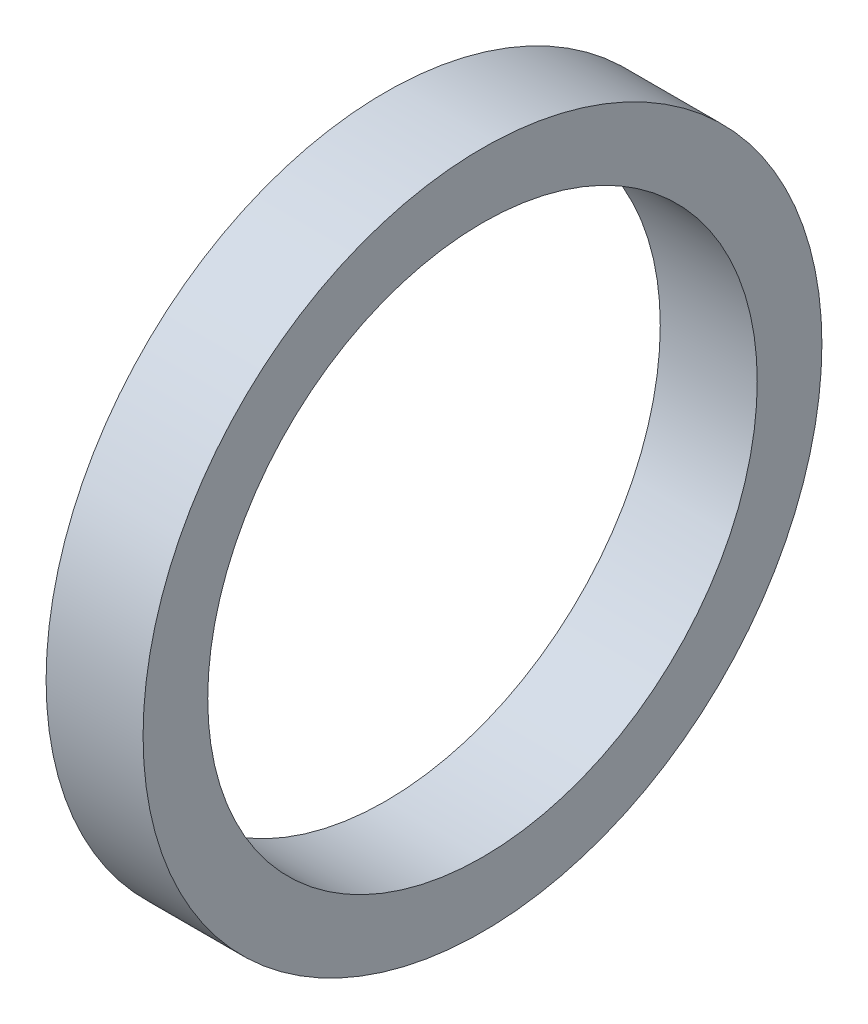
SolidWorks part; units mm, degrees
ref_plane "Front Plane" through (0, 0, 0) normal (0, 0, 1) x (1, 0, 0)
ref_plane "Top Plane" through (0, 0, 0) normal (0, 1, 0) x (1, 0, 0)
ref_plane "Right Plane" through (0, 0, 0) normal (1, 0, 0) x (0, 0, -1)
sketch "Sketch1" plane through (0, 0, 0) normal (1, 0, 0) x (0, 0, -1)
  circle A0 centre (0, 0) radius 26.9875
  circle A1 centre (0, 0) radius 33.3375
extrude "Boss-Extrude1" add sketch "Sketch1" along normal mid plane 9.525
